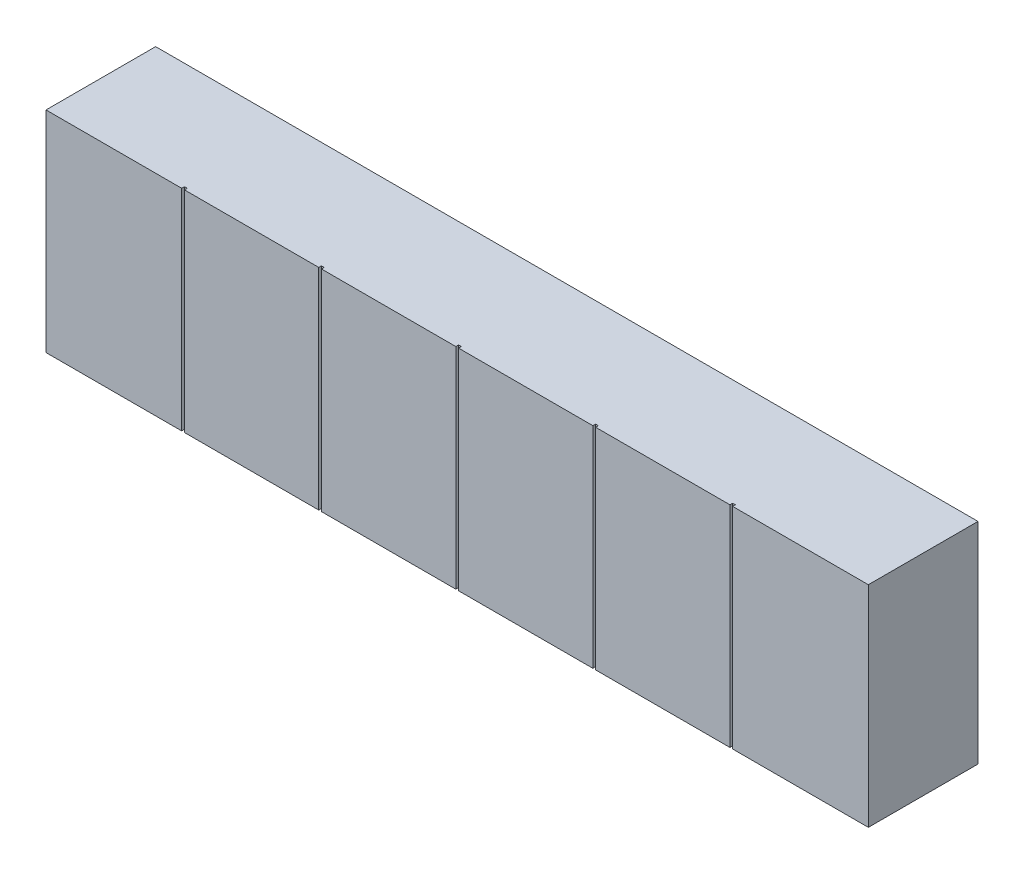
SolidWorks part; units mm, degrees
ref_plane "Front Plane" through (0, 0, 0) normal (0, 0, 1) x (1, 0, 0)
ref_plane "Top Plane" through (0, 0, 0) normal (0, 1, 0) x (1, 0, 0)
ref_plane "Right Plane" through (0, 0, 0) normal (1, 0, 0) x (0, 0, -1)
sketch "Sketch1" plane through (0, 0, 0) normal (0, 0, 1) x (1, 0, 0)
  line L1 (-450, -115) -> (450, -115)
  line L2 (-450, -115) -> (-450, 115)
  line L3 (-450, 115) -> (450, 115)
  line L4 (450, -115) -> (450, 115)
  line L5 (-450, -115) -> (450, 115) construction
  line L6 (-450, 115) -> (450, -115) construction
  point P0 (0, 0)
  dimension "D1" = 230
  dimension "D2" = 900
extrude "Boss-Extrude1" add sketch "Sketch1" along normal blind 120
sketch "Sketch2" plane through (0, 0, 120) normal (0, 0, 1) x (1, 0, 0)
  line L0 (450, 115) -> (-450, 115) construction
  line L1 (-301.5, 115) -> (-298.5, 115)
  line L2 (-301.5, 115) -> (-301.5, -115)
  line L3 (-301.5, -115) -> (-298.5, -115)
  line L4 (-298.5, 115) -> (-298.5, -115)
  line L5 (-450, -115) -> (450, -115) construction
  line L6 (-300, 115) -> (-300, -115) construction
  line L7 (-450, 115) -> (-450, -115) construction
  line L8 (-148.5, 115) -> (-148.5, -115)
  line L9 (-151.5, 115) -> (-148.5, 115)
  line L10 (-151.5, 115) -> (-151.5, -115)
  line L11 (-151.5, -115) -> (-148.5, -115)
  line L12 (1.5, 115) -> (1.5, -115)
  line L13 (-1.5, 115) -> (1.5, 115)
  line L14 (-1.5, 115) -> (-1.5, -115)
  line L15 (-1.5, -115) -> (1.5, -115)
  line L16 (151.5, 115) -> (151.5, -115)
  line L17 (148.5, 115) -> (151.5, 115)
  line L18 (148.5, 115) -> (148.5, -115)
  line L19 (148.5, -115) -> (151.5, -115)
  line L20 (301.5, 115) -> (301.5, -115)
  line L21 (298.5, 115) -> (301.5, 115)
  line L22 (298.5, 115) -> (298.5, -115)
  line L23 (298.5, -115) -> (301.5, -115)
  dimension "D1" = 3
  dimension "D2" = 150
  dimension "D3" = 5
extrude "Cut-Extrude1" cut sketch "Sketch2" against normal blind 3
